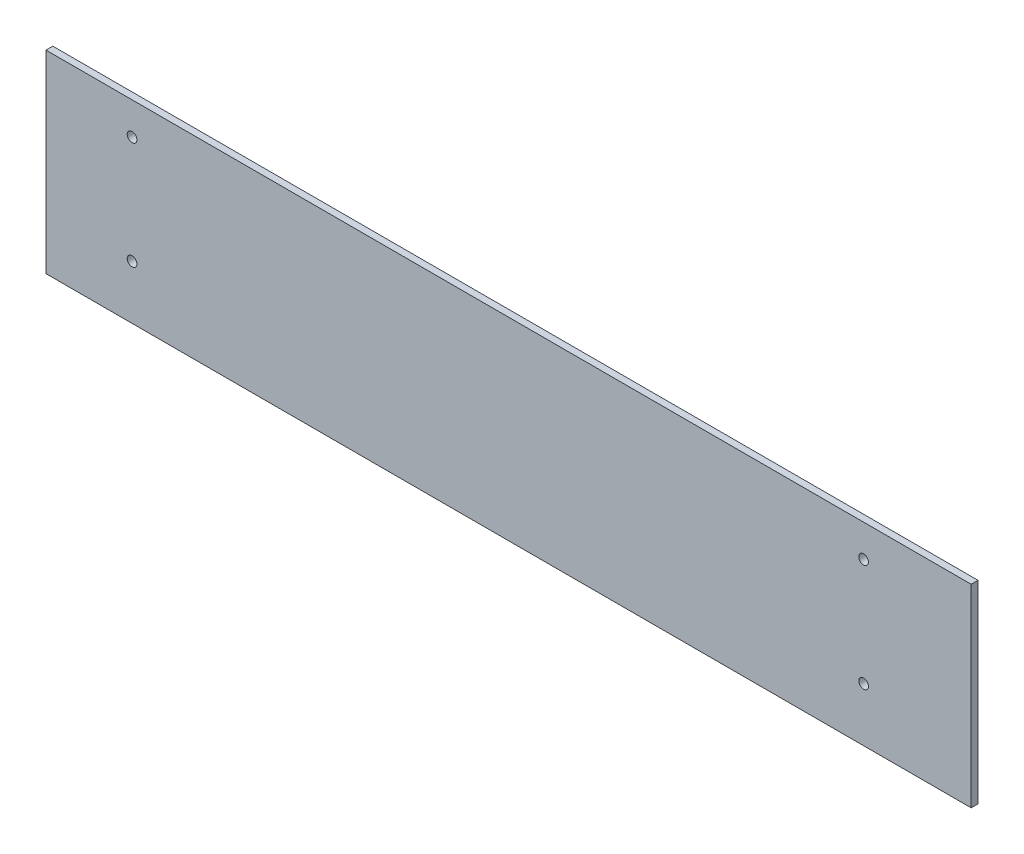
SolidWorks part; units mm, degrees
ref_plane "Front Plane" through (0, 0, 0) normal (0, 0, 1) x (1, 0, 0)
ref_plane "Top Plane" through (0, 0, 0) normal (0, 1, 0) x (1, 0, 0)
ref_plane "Right Plane" through (0, 0, 0) normal (1, 0, 0) x (0, 0, -1)
sketch "Sketch1" plane through (0, 0, 0) normal (0, 0, 1) x (1, 0, 0)
  line L1 (-215, -45) -> (215, -45)
  line L2 (-215, -45) -> (-215, 45)
  line L3 (-215, 45) -> (215, 45)
  line L4 (215, -45) -> (215, 45)
  line L5 (-215, -45) -> (215, 45) construction
  line L6 (-215, 45) -> (215, -45) construction
  point P0 (0, 0)
  dimension "D1" = 430
  dimension "D2" = 90
extrude "Boss-Extrude1" add sketch "Sketch1" along normal blind 3.175
hole_wizard "M4 Clearance Hole1" positions "Sketch2" profile "Sketch3" hole size "M4" standard "ANSI Metric"
sketch "Sketch2" plane through (0, 0, 3.175) normal (0, 0, 1) x (1, 0, 0)
  line L1 (-175, -20) -> (165, -20)
  line L2 (-175, -20) -> (-175, 30)
  line L3 (-175, 30) -> (165, 30)
  line L4 (165, -20) -> (165, 30)
  line L5 (-175, -20) -> (165, 30) construction
  line L6 (-175, 30) -> (165, -20) construction
  line L7 (-215, 45) -> (-215, -45) construction
  line L8 (215, -45) -> (215, 45) construction
  line L9 (-215, -45) -> (215, -45) construction
  point P2 (165, 30)
  point P59 (-175, -20)
  point P60 (-175, 30)
  point P61 (165, -20)
  dimension "D1" = 50
  dimension "D2" = 40
  dimension "D3" = 50
  dimension "D4" = 25
sketch "Sketch3" plane through (165, 30, 3.175) normal (1, 0, 0) x (0, -1, 0)
  line L0 (0, 0) -> (0, 11.4519)
  line L1 (0, 11.4519) -> (2.25, 10.1)
  line L2 (2.25, 10.1) -> (2.25, 0)
  line L5 (2.25, 0) -> (0, 0)
  line L10 (0, 11.4519) -> (-2.25, 10.1) construction
  line L11 (0, -6.35) -> (0, 107.95) construction
  dimension "Hole Dia." = 4.5
  dimension "Hole Depth" = 10.1
  dimension "Drill Angle" = 118
